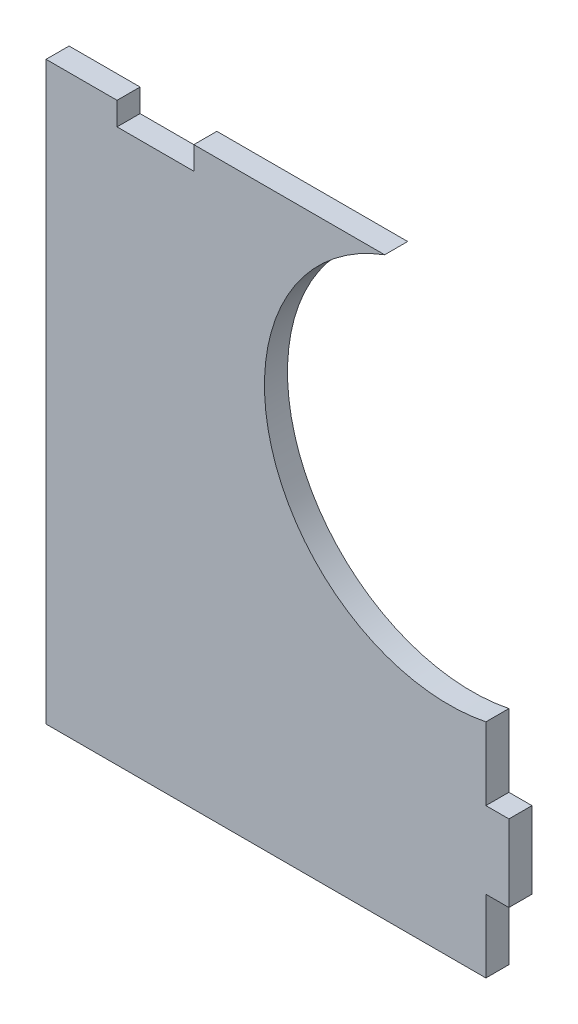
SolidWorks part; units mm, degrees
ref_plane "Alzado" through (0, 0, 0) normal (0, 0, 1) x (1, 0, 0)
ref_plane "Planta" through (0, 0, 0) normal (0, 1, 0) x (1, 0, 0)
ref_plane "Vista lateral" through (0, 0, 0) normal (1, 0, 0) x (0, 0, -1)
sketch "Croquis1" plane through (0, 0, 0) normal (0, 0, 1) x (1, 0, 0)
  line L0 (-3, 0.8384) -> (-60.3, 0.8384)
  line L3 (-60.3, 0.8384) -> (-60.3, 75.8384)
  line L7 (-3, 10.2884) -> (-3, 0.8384)
  line L13 (-3, 20.2884) -> (-3, 29.7384)
  line L23 (-16.1879, 75.8384) -> (-41.05, 75.8384)
  line L24 (-51.05, 75.8384) -> (-60.3, 75.8384)
  line L25 (-51.05, 75.8384) -> (-51.05, 72.8384)
  line L26 (-51.05, 72.8384) -> (-41.05, 72.8384)
  line L27 (-41.05, 72.8384) -> (-41.05, 75.8384)
  line L28 (-3, 20.2884) -> (0, 20.2884)
  line L29 (0, 20.2884) -> (0, 10.2884)
  line L30 (0, 10.2884) -> (-3, 10.2884)
  arc A1 (-3, 29.7384) -> (-16.1879, 75.8384) centre (-7.8, 53.3016) cw
  dimension "D3" = 24.0471
  dimension "D1" = 57.3
  dimension "D2" = 28.9
  dimension "D4" = 9.45
  dimension "D5" = 9.45
  dimension "D6" = 3
extrude "Saliente-Extruir1" add sketch "Croquis1" along normal blind 3
